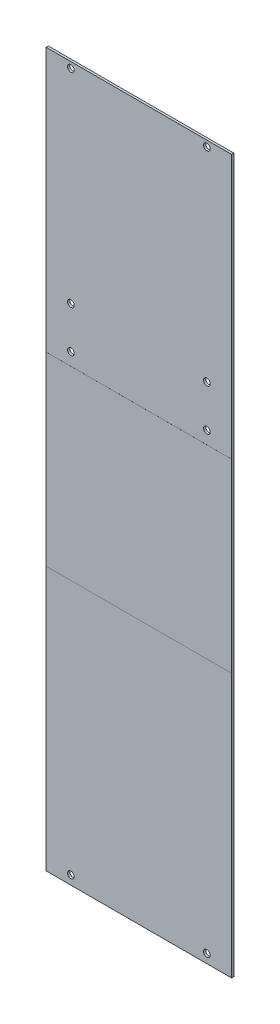
SolidWorks part; units mm, degrees
material "6061 Сплав"
ref_plane "Front Plane" through (0, 0, 0) normal (0, 0, 1) x (1, 0, 0)
ref_plane "Top Plane" through (0, 0, 0) normal (0, 1, 0) x (1, 0, 0)
ref_plane "Right Plane" through (0, 0, 0) normal (1, 0, 0) x (0, 0, -1)
sketch "Sketch1" plane through (0, 0, 0) normal (0, 0, 1) x (1, 0, 0)
  line L1 (41.6, -160) -> (-41.6, -160)
  line L2 (41.6, -160) -> (41.6, 160)
  line L3 (41.6, 160) -> (-41.6, 160)
  line L4 (-41.6, -160) -> (-41.6, 160)
  line L5 (41.6, -160) -> (-41.6, 160) construction
  line L6 (41.6, 160) -> (-41.6, -160) construction
  point P0 (0, 0)
  dimension "D1" = 83.2
  dimension "D2" = 320
extrude "Boss-Extrude1" add sketch "Sketch1" along normal blind 1
hole_wizard "Ø3.0 (3) Diameter Hole1" positions "Sketch3" profile "Sketch2" hole size "Ø3.0" standard "ANSI Metric"
sketch "Sketch3" plane through (0, 0, 1) normal (0, 0, 1) x (1, 0, 0)
  line L6 (-41.6, -160) -> (41.6, -160) construction
  line L9 (41.6, 160) -> (-41.6, 160) construction
  line L10 (0, 160) -> (0, 163.7587) construction
  line L11 (0, 160) -> (0, -152.1509) construction
  point P0 (-30.5, 66)
  point P2 (30.5, 66)
  point P15 (30.5, -156)
  point P17 (-30.5, -156)
  point P54 (-30.5, 157.3)
  point P56 (30.5, 157.3)
  point P58 (-30.5, 47.3)
  point P60 (30.5, 47.3)
  dimension "D2" = 4
  dimension "D3" = 2.7
  dimension "D4" = 4
  dimension "D5" = 30.5
  dimension "D6" = 30.5
  dimension "D7" = 94
  dimension "D8" = 30.5
  dimension "D9" = 2.7
  dimension "D10" = 94
  dimension "D11" = 30.5
  dimension "D12" = 30.5
  dimension "D13" = 30.5
  dimension "D14" = 30.5
  dimension "D15" = 30.5
  dimension "D16" = 112.7
  dimension "D17" = 112.7
sketch "Sketch2" plane through (-30.5, 66, 1) normal (1, 0, 0) x (0, -1, 0)
  line L0 (0, 0) -> (0, 1)
  line L1 (0, 1) -> (1.5, 1)
  line L2 (1.5, 1) -> (1.5, 0)
  line L5 (1.5, 0) -> (0, 0)
  line L10 (0, 1) -> (-1.5, 1) construction
  line L11 (0, -6.35) -> (0, 107.95) construction
  dimension "Hole Dia." = 3
  dimension "Hole Depth" = 1
  dimension "Drill Angle" = 180
sketch "Эскиз1" plane through (0, 0, 1) normal (0, 0, 1) x (1, 0, 0)
  line L0 (41.6, -160) -> (41.6, 160) construction
  line L1 (-41.6, -41.6) -> (41.6, -41.6)
  line L2 (-41.6, -41.6) -> (-41.6, 41.6)
  line L3 (-41.6, 41.6) -> (41.6, 41.6)
  line L4 (41.6, -41.6) -> (41.6, 41.6)
  line L5 (-41.6, -41.6) -> (41.6, 41.6) construction
  line L6 (-41.6, 41.6) -> (41.6, -41.6) construction
  point P0 (0, 0)
  dimension "D1" = 83.2
extrude "Бобышка-Вытянуть1" add sketch "Эскиз1" along normal blind 0.01
